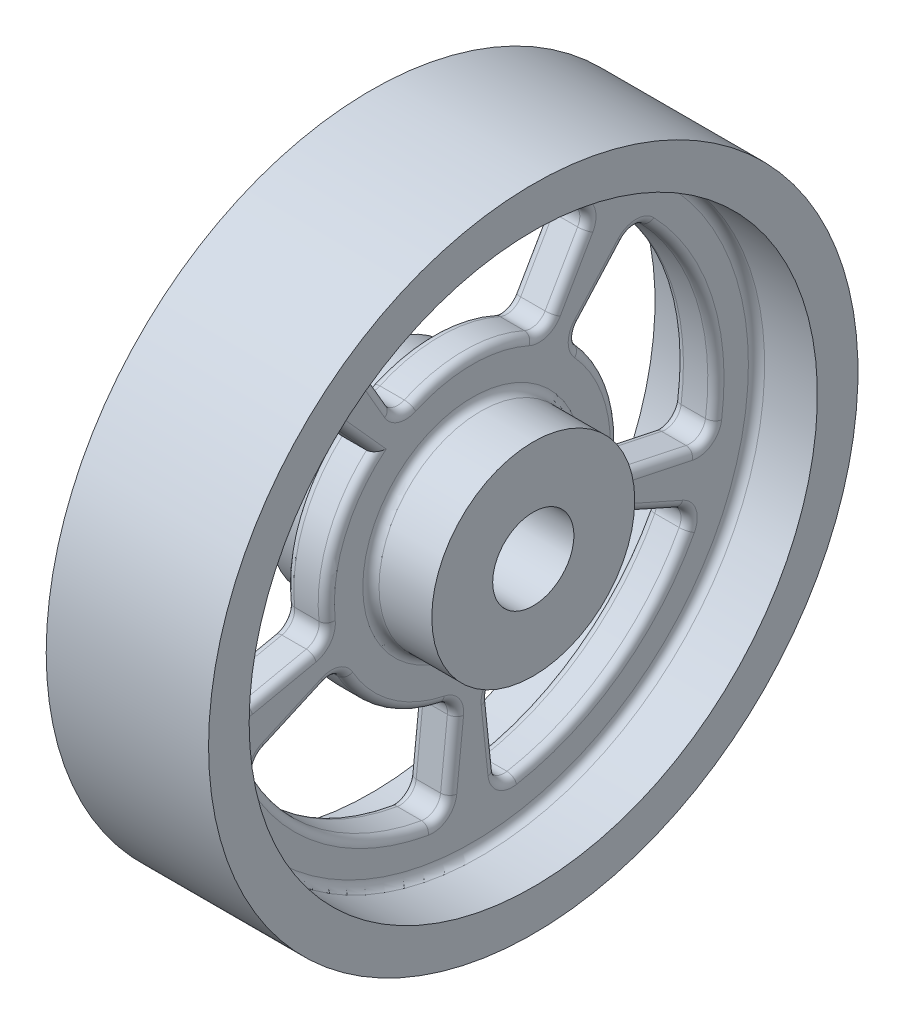
SolidWorks part; units mm, degrees
ref_plane "Front Plane" through (0, 0, 0) normal (0, 0, 1) x (1, 0, 0)
ref_plane "Top Plane" through (0, 0, 0) normal (0, 1, 0) x (1, 0, 0)
ref_plane "Right Plane" through (0, 0, 0) normal (1, 0, 0) x (0, 0, -1)
sketch "Sketch2" plane through (0, 0, 0) normal (0, 0, 1) x (1, 0, 0)
  line L0 (0, 0) -> (37.3494, 0) construction
  line L1 (0, 0) -> (0, 33.5542) construction
  line L2 (2.5, 35) -> (10, 35)
  line L3 (-10, 40) -> (10, 40)
  line L4 (-10, 40) -> (-10, 35)
  line L5 (-10, 35) -> (-2.5, 35)
  line L6 (10, 40) -> (10, 35)
  line L8 (-2.5, 35) -> (-2.5, 12.5)
  line L10 (2.5, 35) -> (2.5, 12.5)
  line L11 (-10, 12.5) -> (-2.5, 12.5)
  line L12 (-10, 12.5) -> (-10, 5)
  line L13 (-10, 5) -> (10, 5)
  line L14 (10, 12.5) -> (10, 5)
  line L15 (2.5, 12.5) -> (10, 12.5)
  dimension "D1" = 10
  dimension "D2" = 25
  dimension "D3" = 80
  dimension "D4" = 20
  dimension "D5" = 5
  dimension "D6" = 5
revolve "Revolve8" add sketch "Sketch2" angle 360 about L0
sketch "Sketch5" plane through (2.5, 0, 0) normal (1, 0, 0) x (0, 0, -1)
  line L0 (0, 0) -> (0, 42.7707) construction
  line L1 (9, 15.5885) -> (15, 25.9808)
  line L2 (-9, 15.5885) -> (-15, 25.9808)
  arc A0 (15, 25.9808) -> (-15, 25.9808) centre (0, 0) ccw
  arc A1 (9, 15.5885) -> (-9, 15.5885) centre (0, 0) ccw
  dimension "D1" = 30
  dimension "D2" = 18
  dimension "D3" = 60
extrude "Cut-Extrude1" cut sketch "Sketch5" against normal blind 10
fillet "Fillet1" radius 2 1 edges at (0, 25.9808, 15)
fillet "Fillet2" radius 2 1 edges at (0, 25.9808, -15)
fillet "Fillet3" radius 2 1 edges at (0, 15.5885, 9)
fillet "Fillet4" radius 2 1 edges at (0, 15.5885, -9)
pattern_circular "CirPattern2" count 5 over 360 about axis through (0, 0, 0) along (1, 0, 0) of "Fillet3", "Cut-Extrude1", "Fillet1", "Fillet2"
fillet "Fillet5" radius 2 1 edges at (0, -3.7424, -17.6067)
fillet "Fillet6" radius 2 1 edges at (0, -17.9014, -1.8815)
fillet "Fillet7" radius 2 1 edges at (0, -7.3213, 16.4438)
fillet "Fillet8" radius 1 41 edges at (2.5, 0, 12.5) (2.5, 0, 35) (2.5, 16.3302, 8.8315) (2.5, 18, 0) (2.5, 16.3302, -8.8315) (2.5, 20.7102, -11.9571) (2.5, 25.7731, -14.1443) (2.5, 30, 0) (2.5, 25.7731, 14.1443) (2.5, 20.7102, 11.9571) (2.5, 13.4456, -12.8018) (2.5, 5.5623, -17.119) (2.5, -3.353, -18.26) (2.5, -4.972, -23.3915) (2.5, -5.4877, -28.8825) (2.5, 9.2705, -28.5317) (2.5, 21.4164, -20.1409) (2.5, 17.7717, -16.0017) (2.5, -8.0203, -16.7435) (2.5, -14.5623, -10.5801) (2.5, -18.4024, -2.4538) (2.5, -23.7831, -2.4997) (2.5, -29.1647, -3.7061) (2.5, -24.2705, -17.6336) (2.5, -12.5371, -26.592) (2.5, -9.7267, -21.8466) (2.5, -18.4024, 2.4538) (2.5, -14.5623, 10.5801) (2.5, -8.0203, 16.7435) (2.5, -9.7267, 21.8466) (2.5, -12.5371, 26.592) (2.5, -24.2705, 17.6336) (2.5, -29.1647, 3.7061) (2.5, -23.7831, 2.4997) (2.5, -3.353, 18.26) (2.5, 6.4124, 16.8191) (2.5, 17.0658, 15.3661) (2.5, 21.4164, 20.1409) (2.5, 9.2705, 28.5317) (2.5, -5.4877, 28.8825) (2.5, -4.972, 23.3915)
fillet "Fillet9" radius 1 41 edges at (-2.5, 0, 35) (-2.5, 0, 12.5) (-2.5, 16.3302, 8.8315) (-2.5, 20.7102, 11.9571) (-2.5, 25.7731, 14.1443) (-2.5, 30, 0) (-2.5, 25.7731, -14.1443) (-2.5, 20.7102, -11.9571) (-2.5, 16.3302, -8.8315) (-2.5, 18, 0) (-2.5, 13.4456, -12.8018) (-2.5, 17.7717, -16.0017) (-2.5, 21.4164, -20.1409) (-2.5, 9.2705, -28.5317) (-2.5, -5.4877, -28.8825) (-2.5, -4.972, -23.3915) (-2.5, -3.353, -18.26) (-2.5, 5.5623, -17.119) (-2.5, -8.0203, -16.7435) (-2.5, -9.7267, -21.8466) (-2.5, -12.5371, -26.592) (-2.5, -24.2705, -17.6336) (-2.5, -29.1647, -3.7061) (-2.5, -23.7831, -2.4997) (-2.5, -18.4024, -2.4538) (-2.5, -14.5623, -10.5801) (-2.5, -18.4024, 2.4538) (-2.5, -23.7831, 2.4997) (-2.5, -29.1647, 3.7061) (-2.5, -24.2705, 17.6336) (-2.5, -12.5371, 26.592) (-2.5, -9.7267, 21.8466) (-2.5, -8.0203, 16.7435) (-2.5, -14.5623, 10.5801) (-2.5, 6.4124, 16.8191) (-2.5, -3.353, 18.26) (-2.5, -4.972, 23.3915) (-2.5, -5.4877, 28.8825) (-2.5, 9.2705, 28.5317) (-2.5, 21.4164, 20.1409) (-2.5, 17.0658, 15.3661)
